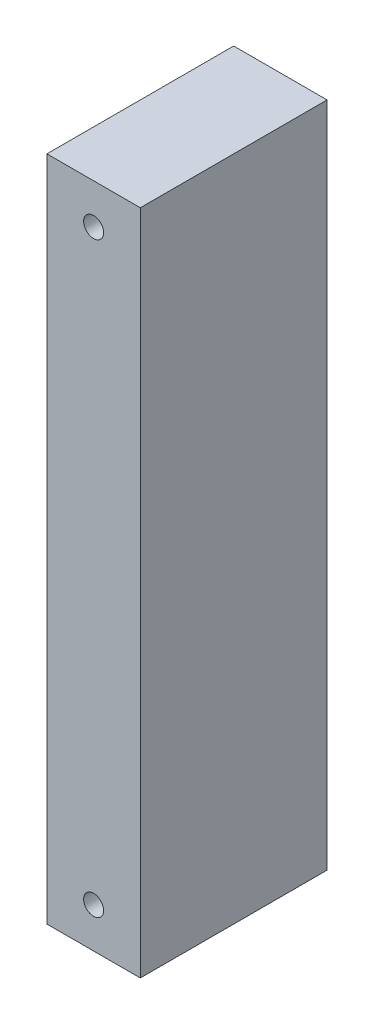
SolidWorks part; units mm, degrees
ref_plane "Front Plane" through (0, 0, 0) normal (0, 0, 1) x (1, 0, 0)
ref_plane "Top Plane" through (0, 0, 0) normal (0, 1, 0) x (1, 0, 0)
ref_plane "Right Plane" through (0, 0, 0) normal (1, 0, 0) x (0, 0, -1)
sketch "Sketch1" plane through (0, 0, 0) normal (0, 0, 1) x (1, 0, 0)
  line L1 (-3.5, -25) -> (3.5, -25)
  line L2 (-3.5, -25) -> (-3.5, 25)
  line L3 (-3.5, 25) -> (3.5, 25)
  line L4 (3.5, -25) -> (3.5, 25)
  line L5 (-3.5, -25) -> (3.5, 25) construction
  line L6 (-3.5, 25) -> (3.5, -25) construction
  circle A0 centre (0, 22) radius 0.75
  circle A1 centre (0, -22) radius 0.75
  point P0 (0, 0)
  dimension "D5" = 1.5
  dimension "D6" = 1.5
  dimension "D1" = 50
  dimension "D2" = 7
  dimension "D3" = 3
  dimension "D4" = 3
extrude "Boss-Extrude1" add sketch "Sketch1" along normal blind 14
